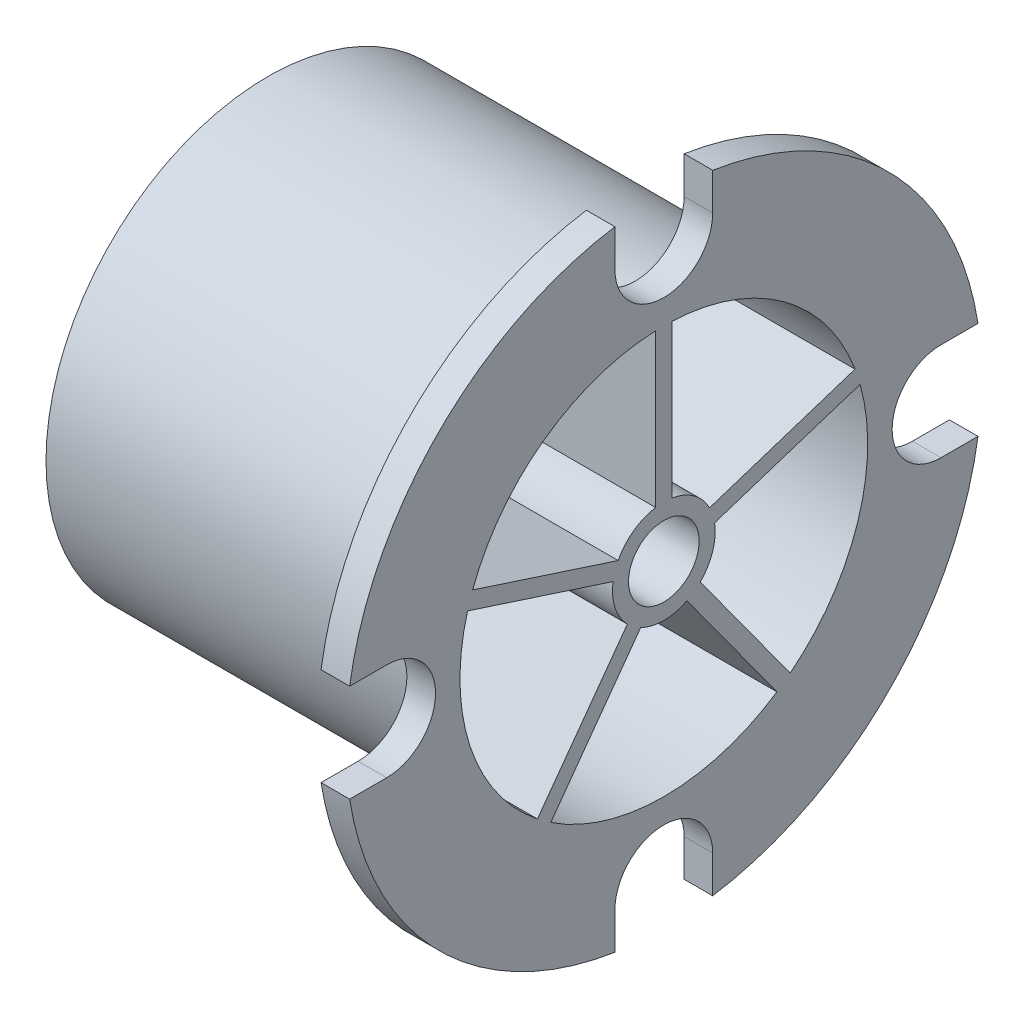
SolidWorks part; units mm, degrees
ref_plane "Front Plane" through (0, 0, 0) normal (0, 0, 1) x (1, 0, 0)
ref_plane "Top Plane" through (0, 0, 0) normal (0, 1, 0) x (1, 0, 0)
ref_plane "Right Plane" through (0, 0, 0) normal (1, 0, 0) x (0, 0, -1)
sketch "Sketch1" plane through (0, 0, 0) normal (1, 0, 0) x (0, 0, -1)
  circle A0 centre (0, 0) radius 34.29
  dimension "D1" = 68.58
extrude "Boss-Extrude1" add sketch "Sketch1" along normal blind 61.214
sketch "Sketch2" plane through (61.214, 0, 0) normal (1, 0, 0) x (0, 0, -1)
  circle A0 centre (0, 0) radius 49.149
  dimension "D1" = 98.298
extrude "Boss-Extrude2" add sketch "Sketch2" against normal blind 4.4196
sketch "Sketch3" plane through (61.214, 0, 0) normal (1, 0, 0) x (0, 0, -1)
  circle A0 centre (0, 0) radius 31.5151
  dimension "D1" = 63.0301
extrude "Cut-Extrude1" cut sketch "Sketch3" against normal blind 24.4094
sketch "Sketch4" plane through (0, 0, 0) normal (-1, 0, 0) x (0, 0, 1)
  circle A0 centre (0, 0) radius 5.461
  dimension "D1" = 10.922
extrude "Cut-Extrude2" cut sketch "Sketch4" against normal through all
sketch "Sketch5" plane through (0, 0, 0) normal (-1, 0, 0) x (0, 0, 1)
  circle A0 centre (0, 0) radius 31.6865
  dimension "D1" = 63.373
extrude "Cut-Extrude3" cut sketch "Sketch5" against normal blind 34.671
sketch "Sketch6" plane through (61.214, 0, 0) normal (1, 0, 0) x (0, 0, -1)
  line L0 (-7.5565, 42.8496) -> (-7.5565, 48.5646)
  line L1 (-7.5565, 48.5646) -> (7.5565, 48.5646) construction
  line L2 (7.5565, 48.5646) -> (7.5565, 42.8496)
  line L3 (0, 0) -> (0, 42.8496) construction
  line L4 (-7.5565, 48.5646) -> (-7.5565, 51.9481)
  line L5 (-7.5565, 51.9481) -> (7.5565, 51.9481)
  line L6 (7.5565, 51.9481) -> (7.5565, 48.5646)
  arc A0 (-7.5565, 42.8496) -> (7.5565, 42.8496) centre (0, 42.8496) ccw
  circle A1 centre (0, 0) radius 49.149 construction
  dimension "D1" = 15.113
  dimension "D2" = 5.715
extrude "Cut-Extrude4" cut sketch "Sketch6" against normal through all
pattern_circular "CirPattern1" count 4 every 90 about axis through (0, 0, 0) along (1, 0, 0) of "Cut-Extrude4"
sketch "Sketch7" plane through (36.8046, 0, 0) normal (1, 0, 0) x (0, 0, -1)
  circle A0 centre (0, 0) radius 7.9375
  circle A1 centre (0, 0) radius 5.461
  circle A2 centre (0, 0) radius 5.461 construction
  dimension "D1" = 2.4765
extrude "Boss-Extrude3" add sketch "Sketch7" along normal up to surface (24.4094 mm away)
sketch "Sketch8" plane through (36.8046, 0, 0) normal (1, 0, 0) x (0, 0, -1)
  line L0 (0, 0) -> (0, 6.0056) construction
  line L1 (-1.27, 34.1358) -> (1.27, 34.1358)
  line L2 (-1.27, 34.1358) -> (-1.27, 6.0056)
  line L3 (-1.27, 6.0056) -> (1.27, 6.0056)
  line L4 (1.27, 34.1358) -> (1.27, 6.0056)
  dimension "D1" = 2.54
extrude "Boss-Extrude4" add sketch "Sketch8" along normal up to surface (24.4094 mm away)
pattern_circular "CirPattern2" count 5 every 72 about axis through (0, 0, 0) along (1, 0, 0) of "Boss-Extrude4"
sketch "Sketch9" plane through (34.671, 0, 0) normal (-1, 0, 0) x (0, 0, 1)
  circle A0 centre (0, 0) radius 7.9629
  circle A1 centre (0, 0) radius 5.461
  circle A2 centre (0, 0) radius 5.461 construction
  dimension "D1" = 2.5019
extrude "Boss-Extrude5" add sketch "Sketch9" along normal blind 22.86
sketch "Sketch10" plane through (34.671, 0, 0) normal (-1, 0, 0) x (0, 0, 1)
  line L0 (-2.9786, 6.2095) -> (-0.5252, 6.8669)
  line L1 (-0.5252, 6.8669) -> (-7.2955, 32.1342)
  line L2 (-7.2955, 32.1342) -> (-9.749, 31.4768)
  line L3 (-9.749, 31.4768) -> (-2.9786, 6.2095)
  line L4 (0, 0) -> (-1.7519, 6.5382) construction
  line L5 (0, 0) -> (0, 35.2931) construction
  arc A0 (-7.5565, 42.8496) -> (7.5565, 42.8496) centre (0, 42.8496) ccw construction
  dimension "D1" = 15
  dimension "D2" = 2.54
extrude "Boss-Extrude6" add sketch "Sketch10" along normal offset from surface (22.3012 mm away) 0.5588 up to face at (11.811, 0, 7.9629)
fillet "Fillet1" radius 0.508 2 edges at (12.3698, 19.4164, -3.8878) (12.3698, 18.759, -6.3413)
sketch "Sketch11" plane through (34.671, 0, 0) normal (-1, 0, 0) x (0, 0, 1)
  line L0 (0, 0) -> (-8.0203, 29.9321) construction
  line L1 (0, 0) -> (0, 35.2931) construction
  arc A0 (-7.5565, 42.8496) -> (7.5565, 42.8496) centre (0, 42.8496) ccw construction
  circle A1 centre (-8.0203, 29.9321) radius 1.651
  circle A2 centre (0, 0) radius 34.29 construction
  dimension "D2" = 3.302
  dimension "D3" = 4.953
  dimension "D1" = 15
extrude "Boss-Extrude7" add sketch "Sketch11" along normal offset from surface (34.925 mm away) 0.254 up to face at (0, 0, 31.6865) offset beyond the face yes
pattern_circular "CirPattern3" count 10 every 36 about axis through (0, 0, 0) along (1, 0, 0) of "Boss-Extrude6", "Fillet1", "Boss-Extrude7"
